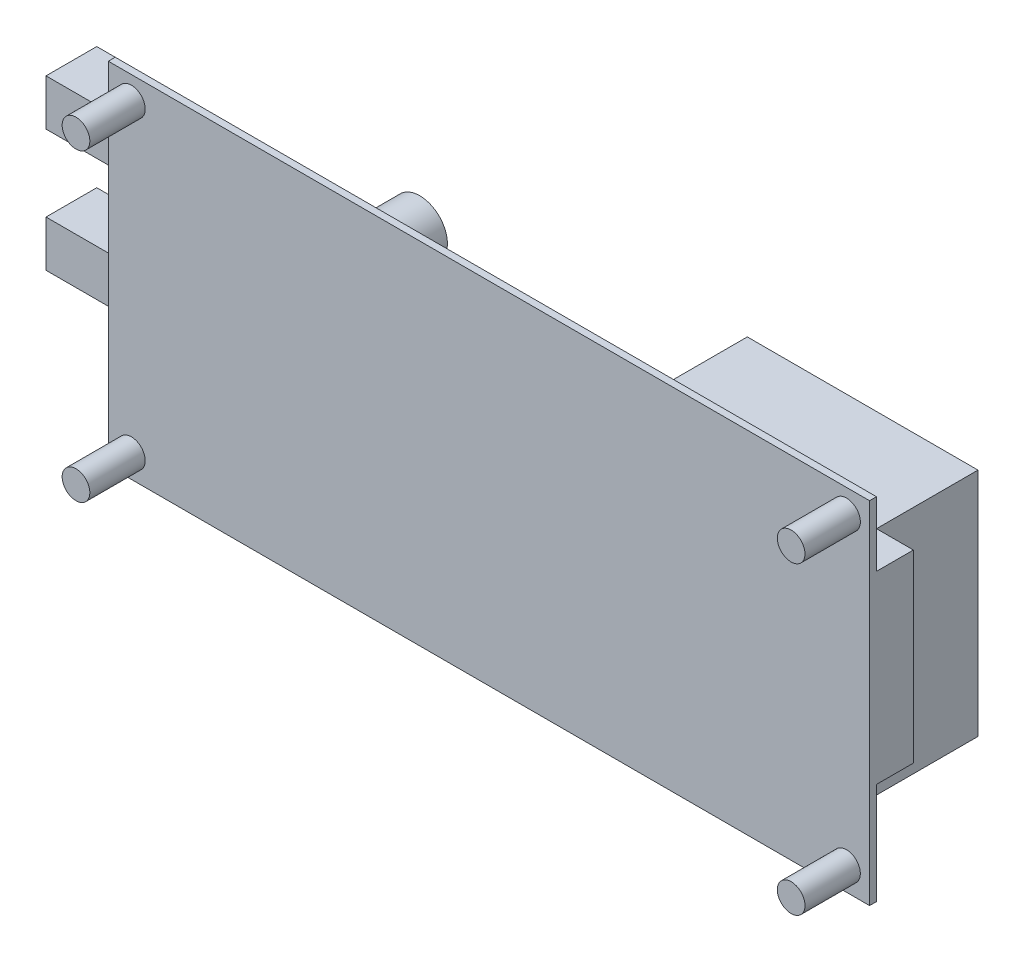
SolidWorks part; units mm, degrees
ref_plane "Front Plane" through (0, 0, 0) normal (0, 0, 1) x (1, 0, 0)
ref_plane "Top Plane" through (0, 0, 0) normal (0, 1, 0) x (1, 0, 0)
ref_plane "Right Plane" through (0, 0, 0) normal (1, 0, 0) x (0, 0, -1)
sketch "Sketch1" plane through (0, 0, 0) normal (0, 0, 1) x (1, 0, 0)
  line L1 (-35.2387, 26.9472) -> (129.7613, 26.9472)
  line L2 (-35.2387, 26.9472) -> (-35.2387, -49.0528)
  line L3 (-35.2387, -49.0528) -> (129.7613, -49.0528)
  line L4 (129.7613, 26.9472) -> (129.7613, -49.0528)
  dimension "D1" = 165
  dimension "D2" = 76
extrude "Boss-Extrude1" add sketch "Sketch1" along normal blind 1.5
sketch "Sketch2" plane through (0, 0, 1.5) normal (0, 0, 1) x (1, 0, 0)
  line L0 (129.7613, 26.9472) -> (-35.2387, 26.9472) construction
  line L1 (129.7613, -49.0528) -> (129.7613, 26.9472) construction
  line L2 (47.2613, 26.9472) -> (47.2613, -49.0528) construction
  line L3 (-35.2387, -49.0528) -> (129.7613, -49.0528) construction
  line L4 (-35.2387, -11.0528) -> (129.7613, -11.0528) construction
  line L5 (-35.2387, 26.9472) -> (-35.2387, -49.0528) construction
  circle A0 centre (124.7613, 21.9472) radius 1.5
  circle A1 centre (124.7613, -44.0528) radius 1.5
  circle A2 centre (-30.2387, -44.0528) radius 1.5
  circle A3 centre (-30.2387, 21.9472) radius 1.5
  dimension "D1" = 3
  dimension "D2" = 5
  dimension "D3" = 5
extrude "Cut-Extrude1" cut sketch "Sketch2" against normal up to next
sketch "Sketch3" plane through (0, 0, 0) normal (0, 0, -1) x (-1, 0, 0)
  line L0 (-129.7613, -49.0528) -> (-129.7613, 26.9472) construction
  line L1 (-129.7613, -27.0528) -> (-117.7613, -27.0528)
  line L2 (-129.7613, -27.0528) -> (-129.7613, 12.9472)
  line L3 (-129.7613, 12.9472) -> (-117.7613, 12.9472)
  line L4 (-117.7613, -27.0528) -> (-117.7613, 12.9472)
  line L5 (-129.7613, 26.9472) -> (35.2387, 26.9472) construction
  dimension "D1" = 12
  dimension "D2" = 40
  dimension "D3" = 14
extrude "Boss-Extrude2" add sketch "Sketch3" along normal blind 8
sketch "Sketch4" plane through (0, 0, 0) normal (0, 0, -1) x (-1, 0, 0)
  line L0 (35.2387, -49.0528) -> (-129.7613, -49.0528) construction
  line L1 (-69.7613, 10.9472) -> (-119.7613, 10.9472)
  line L2 (-69.7613, 10.9472) -> (-69.7613, -39.0528)
  line L3 (-69.7613, -39.0528) -> (-119.7613, -39.0528)
  line L4 (-119.7613, 10.9472) -> (-119.7613, -39.0528)
  line L5 (-129.7613, -49.0528) -> (-129.7613, -27.0528) construction
  dimension "D1" = 50
  dimension "D2" = 50
  dimension "D3" = 10
  dimension "D4" = 10
extrude "Boss-Extrude3" add sketch "Sketch4" along normal blind 32
sketch "Sketch5" plane through (0, 0, 0) normal (0, 0, -1) x (-1, 0, 0)
  line L0 (35.2387, 26.9472) -> (35.2387, -49.0528) construction
  line L1 (50.2387, 5.9472) -> (20.2387, 5.9472)
  line L2 (50.2387, 5.9472) -> (50.2387, 15.9472)
  line L3 (50.2387, 15.9472) -> (20.2387, 15.9472)
  line L4 (20.2387, 5.9472) -> (20.2387, 15.9472)
  line L5 (-129.7613, 26.9472) -> (35.2387, 26.9472) construction
  line L6 (20.2387, -20.5528) -> (50.2387, -20.5528)
  line L7 (20.2387, -20.5528) -> (20.2387, -10.5528)
  line L8 (20.2387, -10.5528) -> (50.2387, -10.5528)
  line L9 (50.2387, -20.5528) -> (50.2387, -10.5528)
  dimension "D1" = 15
  dimension "D2" = 10
  dimension "D3" = 30
  dimension "D4" = 26.5
  dimension "D5" = 11
extrude "Boss-Extrude4" add sketch "Sketch5" along normal blind 11
sketch "Sketch6" plane through (0, 0, 0) normal (0, 0, -1) x (-1, 0, 0)
  line L0 (-129.7613, 26.9472) -> (35.2387, 26.9472) construction
  line L1 (35.2387, 5.9472) -> (35.2387, -10.5528) construction
  circle A0 centre (-5.7613, 2.9472) radius 6
  dimension "D1" = 12
  dimension "D2" = 24
  dimension "D3" = 41
extrude "Boss-Extrude5" add sketch "Sketch6" along normal blind 25
sketch "Sketch7" plane through (0, 0, 1.5) normal (0, 0, 1) x (1, 0, 0)
  line L0 (129.7613, -49.0528) -> (129.7613, 26.9472) construction
  line L1 (129.7613, -11.0528) -> (-35.2387, -11.0528) construction
  line L2 (-35.2387, 26.9472) -> (-35.2387, -49.0528) construction
  line L3 (47.2613, 26.9472) -> (47.2613, -49.0528) construction
  line L4 (129.7613, 26.9472) -> (-35.2387, 26.9472) construction
  line L5 (-35.2387, -49.0528) -> (129.7613, -49.0528) construction
  circle A0 centre (124.7613, 21.9472) radius 3
  circle A1 centre (124.7613, 21.9472) radius 1.5 construction
  circle A3 centre (124.7613, -44.0528) radius 3
  circle A4 centre (-30.2387, 21.9472) radius 3
  circle A5 centre (-30.2387, -44.0528) radius 3
  dimension "D1" = 6
extrude "Boss-Extrude6" add sketch "Sketch7" along normal blind 12
